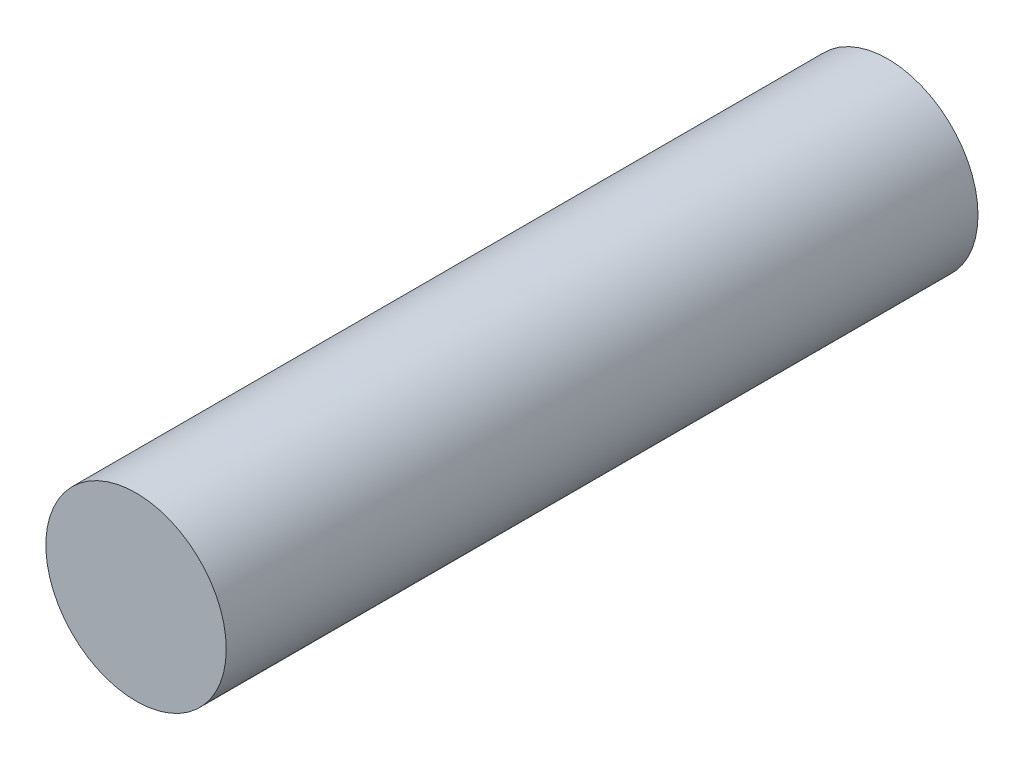
SolidWorks part; units mm, degrees
ref_plane "前视基准面" through (0, 0, 0) normal (0, 0, 1) x (1, 0, 0)
ref_plane "上视基准面" through (0, 0, 0) normal (0, 1, 0) x (1, 0, 0)
ref_plane "右视基准面" through (0, 0, 0) normal (1, 0, 0) x (0, 0, -1)
sketch "草图1" plane through (0, 0, 0) normal (0, 0, 1) x (1, 0, 0)
  circle A0 centre (0, 0) radius 6
  dimension "D1" = 12
extrude "凸台-拉伸1" add sketch "草图1" along normal blind 50
